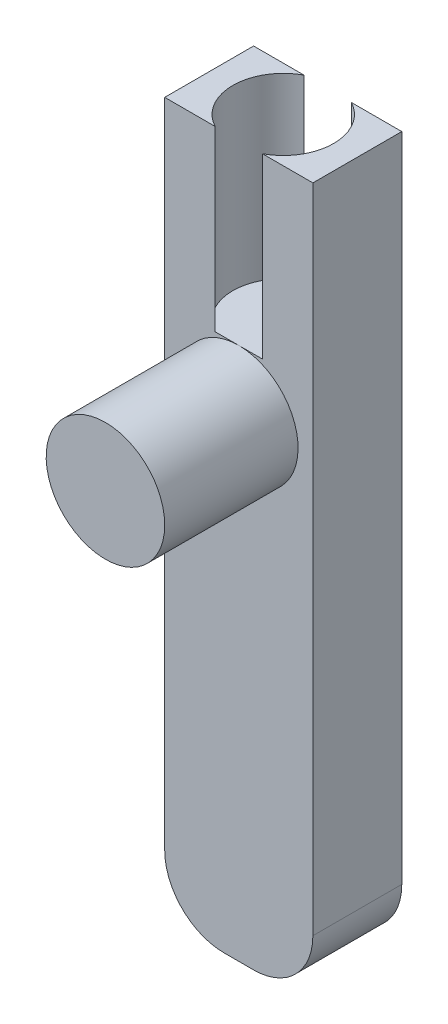
SolidWorks part; units mm, degrees
ref_plane "Спереди" through (0, 0, 0) normal (0, 0, 1) x (1, 0, 0)
ref_plane "Сверху" through (0, 0, 0) normal (0, 1, 0) x (1, 0, 0)
ref_plane "Справа" through (0, 0, 0) normal (1, 0, 0) x (0, 0, -1)
sketch "Эскиз1" plane through (0, 0, 0) normal (0, 0, 1) x (1, 0, 0)
  line L1 (-1, 0) -> (-1.5, 0)
  line L2 (0, 1) -> (0, 12)
  line L3 (0, 12) -> (-2.5, 12)
  line L4 (-2.5, 1) -> (-2.5, 12)
  arc A0 (-1, 0) -> (0, 1) centre (-1, 1) ccw
  arc A1 (-1.5, 0) -> (-2.5, 1) centre (-1.5, 1) cw
  point P7 (0, 0)
  point P10 (-2.5, 0)
  dimension "D3" = 1
  dimension "D1" = 12
  dimension "D2" = 2.5
extrude "Бобышка-Вытянуть1" add sketch "Эскиз1" along normal blind 1.5
sketch "Эскиз2" plane through (0, 0, 1.5) normal (0, 0, 1) x (1, 0, 0)
  line L0 (-1.25, 12) -> (-1.25, 8) construction
  line L1 (0, 12) -> (-2.5, 12) construction
  circle A0 centre (-1.25, 8) radius 1
  dimension "D2" = 2
  dimension "D1" = 4
extrude "Бобышка-Вытянуть2" add sketch "Эскиз2" along normal blind 2.25
sketch "Эскиз3" plane through (0, 12, 0) normal (0, 1, 0) x (1, 0, 0)
  line L0 (-2.5, -1.5) -> (0, 0) construction
  circle A0 centre (-1.25, -0.75) radius 0.85
  dimension "D1" = 1.7
extrude "Вырез-Вытянуть1" cut sketch "Эскиз3" against normal blind 3
